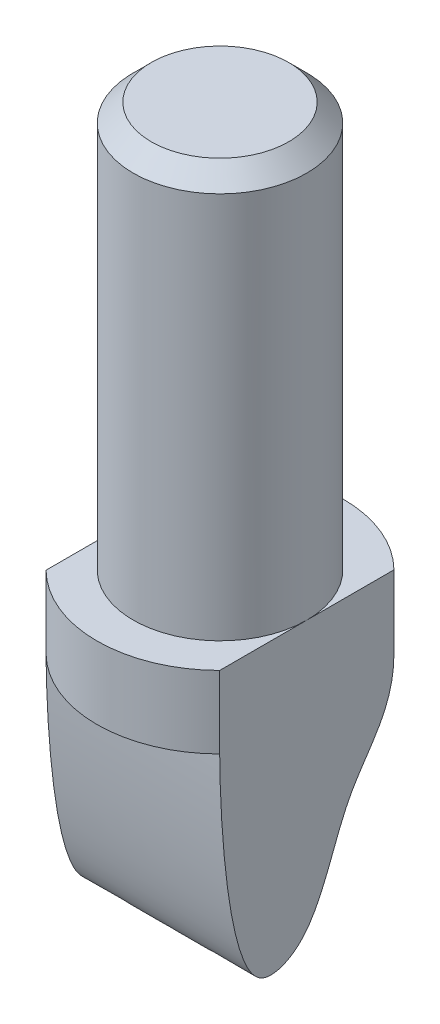
SolidWorks part; units mm, degrees
ref_plane "Front Plane" through (0, 0, 0) normal (0, 0, 1) x (1, 0, 0)
ref_plane "Top Plane" through (0, 0, 0) normal (0, 1, 0) x (1, 0, 0)
ref_plane "Right Plane" through (0, 0, 0) normal (1, 0, 0) x (0, 0, -1)
sketch "Sketch1" plane through (0, 0, 0) normal (0, 1, 0) x (1, 0, 0)
  circle A0 centre (0, 0) radius 1.2
  dimension "D1" = 2.4
extrude "Boss-Extrude3" add sketch "Sketch1" along normal blind 6.6
chamfer "Chamfer1" distance 0.25 angle 45 1 edges at (0, 6.6, 1.2)
sketch "Sketch3" plane through (0, 0, 0) normal (0, 1, 0) x (1, 0, 0)
  line L0 (-1.2, -1.2042) -> (-1.2, 1.2042)
  line L1 (1.2, -1.2042) -> (1.2, 1.2042)
  circle A0 centre (0, 0) radius 1.7
  circle A1 centre (0, 0) radius 1.2
  circle A2 centre (0, 0) radius 1.2 construction
  dimension "D1" = 0
  dimension "D2" = 0.5
extrude "Boss-Extrude4" add sketch "Sketch3" along normal blind 1 contours L1 A0 L0
sketch "Sketch2" plane through (0, 0, 0) normal (1, 0, 0) x (0, 0, -1)
  line L0 (-1.2042, 0) -> (1.2042, 0) construction
  line L1 (-1.2042, 0) -> (1.2042, 0)
  line L2 (1.2042, -0.5924) -> (1.2042, 0.5924) construction
  line L3 (-1.2042, 1.0415) -> (-1.2042, -1.0415) construction
  spline S0 degree 3 poles (1.2042, 0) (1.2042, -0.6667) (0.4025, -1.2898) (0.1607, -2.9308) (-1.1049, -3.0933) (-1.2042, -0.6) (-1.2042, 0) knots 0 0 0 0 0.278965 0.615717 0.68782 1 1 1 1
  dimension "D1" = 2
  dimension "D2" = 2
  dimension "D3" = 0.5
  dimension "D4" = 3
extrude "Boss-Extrude5" add sketch "Sketch2" along normal up to surface and the other way up to surface contours S0 L1 up to face at (1.2, 0.6, 0) other way up to face at (-1.2, 0.6, 0)
